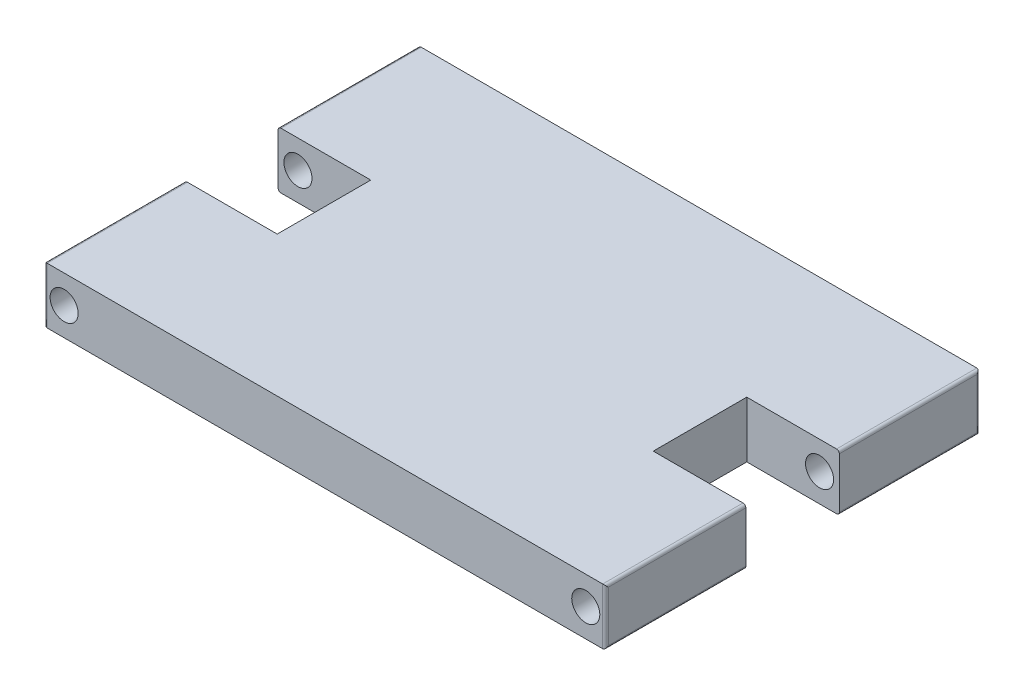
SolidWorks part; units mm, degrees
ref_plane "Piano frontale" through (0, 0, 0) normal (0, 0, 1) x (1, 0, 0)
ref_plane "Piano superiore" through (0, 0, 0) normal (0, 1, 0) x (1, 0, 0)
ref_plane "Piano destro" through (0, 0, 0) normal (1, 0, 0) x (0, 0, -1)
sketch "Schizzo1" plane through (0, 0, 0) normal (0, 1, 0) x (1, 0, 0)
  line L1 (3, 0) -> (597, 0)
  line L2 (0, 3) -> (0, 397)
  line L3 (3, 400) -> (597, 400)
  line L4 (600, 3) -> (600, 397)
  arc A0 (597, 400) -> (600, 397) centre (597, 397) cw
  arc A1 (597, 0) -> (600, 3) centre (597, 3) ccw
  arc A2 (3, 0) -> (0, 3) centre (3, 3) cw
  arc A3 (0, 397) -> (3, 400) centre (3, 397) cw
  point P7 (600, 400)
  point P12 (0, 0)
  point P15 (0, 400)
  dimension "D3" = 3
  dimension "D1" = 600
  dimension "D2" = 400
extrude "Estrusione-Estrusione1" add sketch "Schizzo1" along normal blind 60
sketch "Schizzo3" plane through (0, 0, 0) normal (0, 0, 1) x (1, 0, 0)
  line L0 (3, 60) -> (597, 60)
  line L1 (600, 57) -> (600, 3)
  line L2 (597, 0) -> (3, 0)
  line L3 (0, 3) -> (0, 57)
  line L4 (0, 30) -> (600, 30) construction
  line L5 (300, 60) -> (300, 0) construction
  arc A0 (597, 60) -> (600, 57) centre (597, 57) cw
  arc A1 (600, 3) -> (597, 0) centre (597, 3) cw
  arc A2 (3, 0) -> (0, 3) centre (3, 3) cw
  arc A3 (3, 60) -> (0, 57) centre (3, 57) ccw
  circle A4 centre (21.15, 30) radius 15
  circle A5 centre (578.85, 30) radius 15
  point P11 (600, 60)
  point P14 (600, 0)
  point P17 (0, 0)
  point P20 (0, 60)
  dimension "D1" = 3
  dimension "D2" = 30
  dimension "D3" = 30
  dimension "D4" = 557.7
  dimension "D5" = 278.85
extrude "Taglio-Estrusione2" cut sketch "Schizzo3" against normal through all both and the other way through all flip side to cut
sketch "Schizzo4" plane through (0, 0, 0) normal (0, 1, 0) x (1, 0, 0)
  line L0 (0, 200) -> (600, 200) construction
  line L1 (0, 397) -> (0, 3) construction
  line L2 (600, 397) -> (600, 3) construction
  line L4 (-1, 250) -> (99, 250)
  line L5 (-1, 250) -> (-1, 150)
  line L6 (-1, 150) -> (99, 150)
  line L7 (99, 250) -> (99, 150)
  line L8 (501, 250) -> (601, 250)
  line L9 (501, 250) -> (501, 150)
  line L10 (501, 150) -> (601, 150)
  line L11 (601, 250) -> (601, 150)
  dimension "D1" = 100
  dimension "D2" = 100
  dimension "D3" = 50
  dimension "D4" = 100
  dimension "D5" = 100
  dimension "D6" = 50
  dimension "D7" = 1
  dimension "D8" = 1
extrude "Taglio-Estrusione3" cut sketch "Schizzo4" along normal through all
